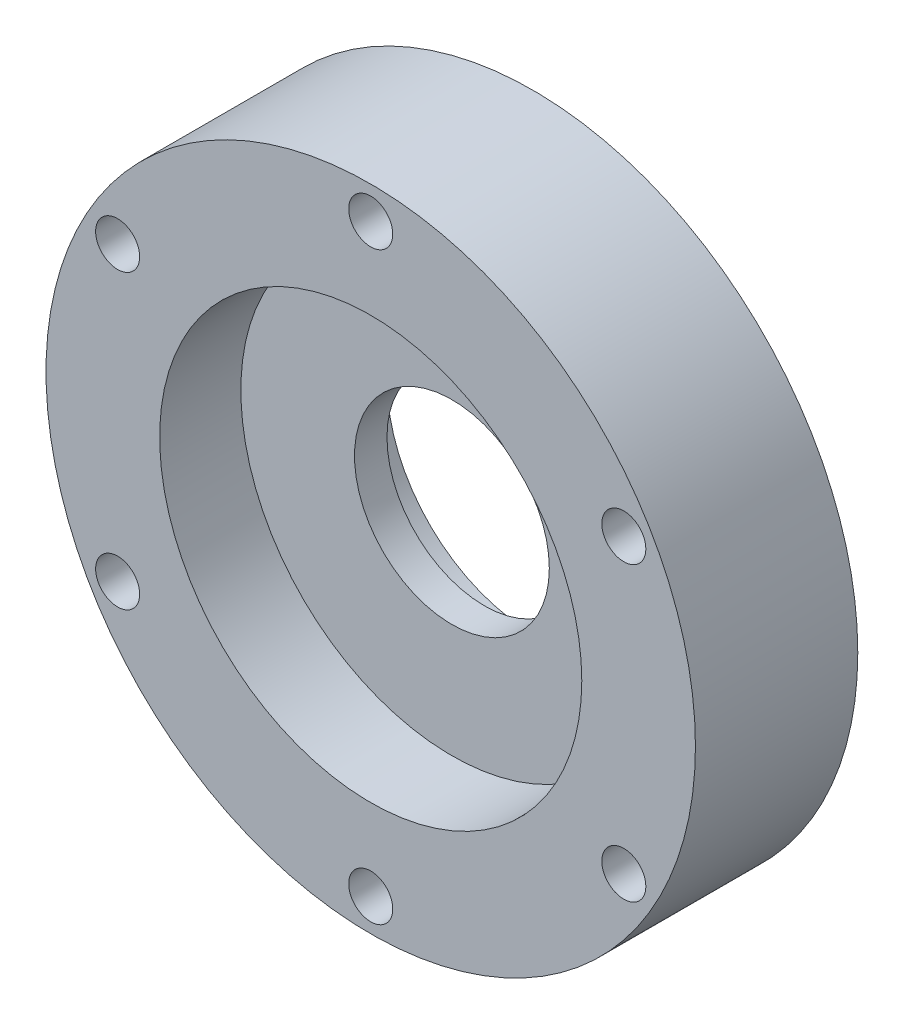
SolidWorks part; units mm, degrees
material "6061-T6 (SS)"
ref_plane "Front Plane" through (0, 0, 0) normal (0, 0, 1) x (1, 0, 0)
ref_plane "Top Plane" through (0, 0, 0) normal (0, 1, 0) x (1, 0, 0)
ref_plane "Right Plane" through (0, 0, 0) normal (1, 0, 0) x (0, 0, -1)
sketch "Sketch1" plane through (0, 0, 0) normal (0, 0, 1) x (1, 0, 0)
  circle A0 centre (0, 0) radius 31.75
  dimension "D1" = 63.5
extrude "Boss-Extrude1" add sketch "Sketch1" along normal blind 15.875
sketch "Sketch2" plane through (0, 0, 15.875) normal (0, 0, 1) x (1, 0, 0)
  circle A0 centre (0, 0) radius 20.6375
  dimension "D1" = 41.275
extrude "Cut-Extrude1" cut sketch "Sketch2" against normal blind 7.9375
sketch "Sketch3" plane through (0, 0, 0) normal (0, 0, -1) x (-1, 0, 0)
  circle A0 centre (0, 0) radius 14.2875
  dimension "D1" = 28.575
extrude "Cut-Extrude2" cut sketch "Sketch3" against normal blind 4.7625
sketch "Sketch4" plane through (0, 0, 7.9375) normal (0, 0, 1) x (1, 0, 0)
  circle A0 centre (0, 0) radius 9.525
  dimension "D1" = 19.05
extrude "Cut-Extrude3" cut sketch "Sketch4" against normal through all
hole_wizard "#8 Clearance Hole1" positions "Sketch6" profile "Sketch7" hole size "#8" standard "Ansi Inch" end condition through all
sketch "Sketch6" plane through (0, 0, 15.875) normal (0, 0, 1) x (1, 0, 0)
  point P0 (0, 28.575)
  point P9 (24.7467, 14.2875)
  point P10 (24.7467, -14.2875)
  point P11 (0, -28.575)
  point P12 (-24.7467, -14.2875)
  point P13 (-24.7467, 14.2875)
  dimension "D1" = 28.575
sketch "Sketch7" plane through (0, 28.575, 15.875) normal (1, 0, 0) x (0, -1, 0)
  line L0 (0, 0) -> (0, 15.875)
  line L1 (0, 15.875) -> (2.1526, 15.875)
  line L2 (2.1526, 15.875) -> (2.1526, 0)
  line L5 (2.1526, 0) -> (0, 0)
  line L11 (0, -6.35) -> (0, 107.95) construction
  dimension "Thru Hole Dia." = 4.3053
  dimension "Thru Hole Depth" = 15.875
sketch "Sketch8" plane through (0, 0, 0) normal (0, 0, -1) x (-1, 0, 0)
  line L0 (0, 26.4224) -> (0, 22.225)
  line L1 (24.7467, 14.2875) -> (18.8416, 10.8782)
  line L2 (0.7874, 24.4469) -> (0.7874, 23.6938)
  line L3 (20.7779, 12.9054) -> (20.1257, 12.5288)
  arc A0 (23.2539, 19.2102) -> (5.0096, 29.7436) centre (0, 0) ccw
  arc A1 (18.0432, 12.9767) -> (2.2166, 22.1142) centre (0, 0) ccw
  arc A2 (1.5833, 25.8229) -> (3.164, 28.3104) centre (0, 28.575) ccw
  arc A3 (22.9356, 16.8953) -> (21.5717, 14.2826) centre (24.7467, 14.2875) ccw
  circle A4 centre (0, 28.575) radius 2.1526 construction
  arc A5 (23.2539, 19.2102) -> (22.9356, 16.8953) centre (22.03, 18.1992) cw
  arc A6 (21.5717, 14.2826) -> (20.7779, 12.9054) centre (19.9842, 14.2802) cw
  arc A7 (20.1257, 12.5288) -> (18.0432, 12.9767) centre (19.332, 13.9036) cw
  arc A8 (2.2166, 22.1142) -> (0.7874, 23.6938) centre (2.3749, 23.6938) cw
  arc A9 (0.7874, 24.4469) -> (1.5833, 25.8229) centre (2.3749, 24.4469) cw
  arc A10 (3.164, 28.3104) -> (5.0096, 29.7436) centre (4.7459, 28.1781) cw
  point P24 (18.8416, 11.7874)
  dimension "D1" = 60.325
  dimension "D2" = 44.45
  dimension "D3" = 6.35
  dimension "D4" = 6.35
  dimension "D7" = 1.5875
  dimension "D5" = 0.7874
  dimension "D6" = 0.7874
extrude "Cut-Extrude4" cut sketch "Sketch8" against normal blind 12.7 contours A10 A2 A9 L2 A8 A1 A7 L3 A6 A3 A5 A0
pattern_circular "CirPattern1" count 6 over 360 about axis through (0, 0, 0) along (0, 0, 1) of "Cut-Extrude4"
sketch "Sketch9" plane through (0, 0, 0) normal (0, 0, -1) x (-1, 0, 0)
  line L0 (0, 24.2331) -> (0, 15.875)
  line L1 (24.7467, 14.2875) -> (13.3375, 7.7004)
  line L2 (0.7874, 24.4469) -> (0.7874, 17.3003)
  line L3 (20.7779, 12.9054) -> (14.5888, 9.332)
  arc A0 (23.2539, 19.2102) -> (5.0096, 29.7436) centre (0, 0) ccw
  arc A1 (12.5409, 9.7335) -> (2.159, 15.7275) centre (0, 0) ccw
  arc A2 (1.5833, 25.8229) -> (3.164, 28.3104) centre (0, 28.575) ccw
  arc A3 (22.9356, 16.8953) -> (21.5717, 14.2826) centre (24.7467, 14.2875) ccw
  arc A5 (23.2539, 19.2102) -> (22.9356, 16.8953) centre (22.03, 18.1992) cw
  arc A6 (21.5717, 14.2826) -> (20.7779, 12.9054) centre (19.9842, 14.2802) cw
  arc A7 (14.5888, 9.332) -> (12.5409, 9.7335) centre (13.795, 10.7069) cw
  arc A8 (2.159, 15.7275) -> (0.7874, 17.3003) centre (2.3749, 17.3003) cw
  arc A9 (0.7874, 24.4469) -> (1.5833, 25.8229) centre (2.3749, 24.4469) cw
  arc A10 (3.164, 28.3104) -> (5.0096, 29.7436) centre (4.7459, 28.1781) cw
  circle A11 centre (0, 0) radius 31.75 construction
  circle A12 centre (24.7467, 14.2875) radius 2.1526 construction
  circle A13 centre (0, 28.575) radius 2.1526 construction
  point P24 (13.3375, 8.6096)
  dimension "D1" = 60.325
  dimension "D2" = 15.875
  dimension "D3" = 6.35
  dimension "D4" = 6.35
  dimension "D7" = 1.5875
  dimension "D5" = 0.7874
  dimension "D6" = 0.7874
extrude "Cut-Extrude5" cut sketch "Sketch9" against normal blind 4.7625 contours A10 A2 A9 L2 A8 A1 A7 L3 A6 A3 A5 A0
pattern_circular "CirPattern2" count 6 over 360 about axis through (0, 0, 0) along (0, 0, 1) of "Cut-Extrude5"
